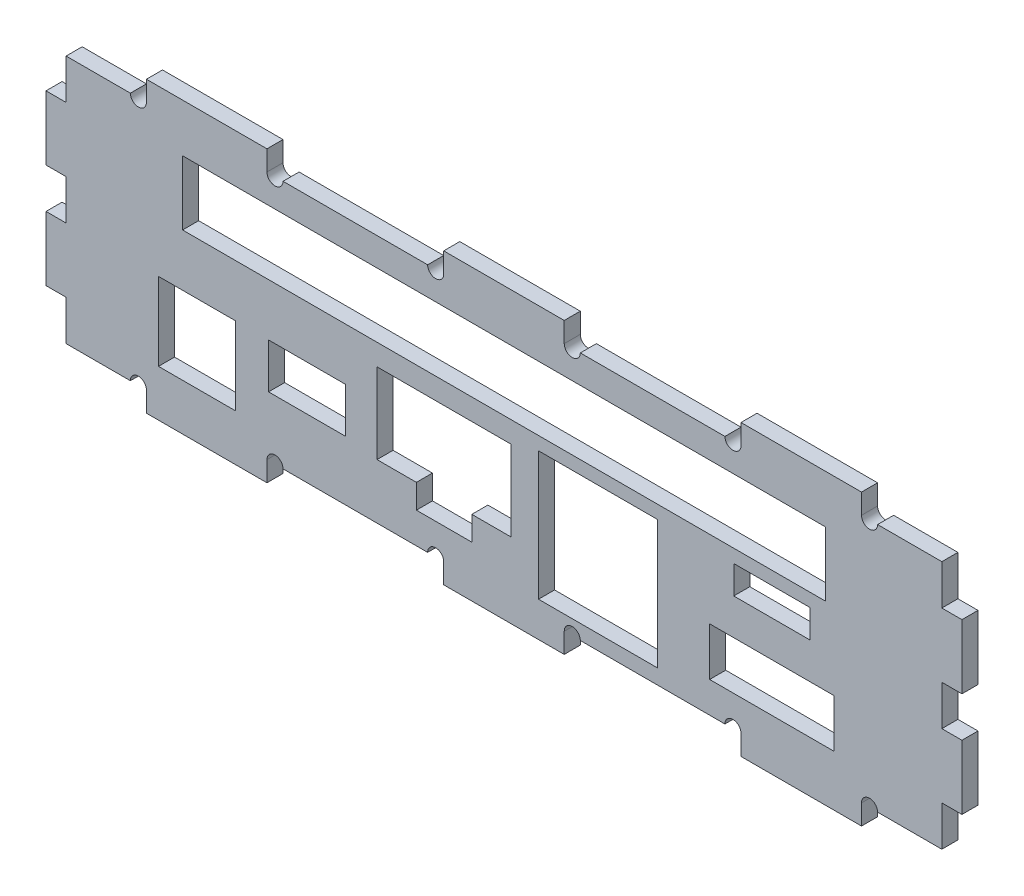
SolidWorks part; units mm, degrees
ref_plane "前视基准面" through (0, 0, 0) normal (0, 0, 1) x (1, 0, 0)
ref_plane "上视基准面" through (0, 0, 0) normal (0, 1, 0) x (1, 0, 0)
ref_plane "右视基准面" through (0, 0, 0) normal (1, 0, 0) x (0, 0, -1)
sketch "草图1" plane through (0, 0, 0) normal (0, 0, 1) x (1, 0, 0)
  line L0 (27.2, 3.55) -> (32.1, 3.55)
  line L1 (0, 0) -> (9.6, 0)
  line L2 (0, 0) -> (0, 9.7)
  line L3 (0, 9.7) -> (9.6, 9.7)
  line L4 (9.6, 0) -> (9.6, 9.7)
  line L5 (13.7, 9.7) -> (23.3, 9.7)
  line L6 (13.7, 9.7) -> (13.7, 4.1)
  line L7 (13.7, 4.1) -> (23.3, 4.1)
  line L8 (23.3, 9.7) -> (23.3, 4.1)
  line L10 (27.2, 3.55) -> (27.2, 13.55)
  line L11 (27.2, 13.55) -> (43.9, 13.55)
  line L12 (43.9, 3.55) -> (43.9, 13.55)
  line L13 (32.1, 3.55) -> (32.1, 0.55)
  line L14 (32.1, 0.55) -> (39, 0.55)
  line L15 (39, 0.55) -> (39, 3.55)
  line L16 (39, 3.55) -> (43.9, 3.55)
  line L18 (47.3, 14.55) -> (62.1, 14.55)
  line L19 (47.3, 14.55) -> (47.3, -1.45)
  line L20 (47.3, -1.45) -> (62.1, -1.45)
  line L21 (62.1, 14.55) -> (62.1, -1.45)
  line L22 (71.6, 14.55) -> (81.1, 14.55)
  line L23 (71.6, 14.55) -> (71.6, 11.05)
  line L24 (71.6, 11.05) -> (81.1, 11.05)
  line L25 (81.1, 14.55) -> (81.1, 11.05)
  line L26 (68.6, 6.55) -> (84.1, 6.55)
  line L27 (68.6, 6.55) -> (68.6, 0.55)
  line L28 (68.6, 0.55) -> (84.1, 0.55)
  line L29 (84.1, 6.55) -> (84.1, 0.55)
  line L30 (3, 16.2) -> (83, 16.2)
  line L31 (3, 16.2) -> (3, 24.2)
  line L32 (3, 24.2) -> (83, 24.2)
  line L33 (83, 16.2) -> (83, 24.2)
  line L34 (-11.5, -3.3) -> (97.5, -3.3)
  line L35 (-11.5, -3.3) -> (-11.5, 27.7)
  line L36 (-11.5, 27.7) -> (97.5, 27.7)
  line L37 (97.5, -3.3) -> (97.5, 27.7)
  dimension "D1" = 9.6
  dimension "D2" = 9.7
  dimension "D3" = 9.6
  dimension "D4" = 4.1
  dimension "D5" = 5.6
  dimension "D6" = 3.9
  dimension "D7" = 10
  dimension "D8" = 6.15
  dimension "D9" = 16.7
  dimension "D10" = 4.9
  dimension "D11" = 3
  dimension "D12" = 3.4
  dimension "D13" = 14.8
  dimension "D14" = 11
  dimension "D15" = 16
  dimension "D16" = 6.5
  dimension "D17" = 6
  dimension "D18" = 2
  dimension "D19" = 15.5
  dimension "D20" = 9.5
  dimension "D21" = 3
  dimension "D22" = 3.5
  dimension "D23" = 14.5
  dimension "D24" = 8
  dimension "D25" = 3
  dimension "D26" = 80
  dimension "D27" = 109
  dimension "D28" = 3.5
  dimension "D29" = 31
  dimension "D30" = 14.5
extrude "凸台-拉伸1" add sketch "草图1" along normal blind 2
sketch "草图2" plane through (0, 0, 2) normal (0, 0, 1) x (1, 0, 0)
  line L0 (-11.5, 27.7) -> (-11.5, -3.3) construction
  line L1 (-11.5, 22.7) -> (-14, 22.7)
  line L2 (-11.5, 22.7) -> (-11.5, 14.7)
  line L3 (-11.5, 14.7) -> (-14, 14.7)
  line L4 (-14, 22.7) -> (-14, 14.7)
  line L5 (97.5, 27.7) -> (-11.5, 27.7) construction
  line L6 (-11.5, 9.7) -> (-14, 9.7)
  line L7 (-11.5, 9.7) -> (-11.5, 1.7)
  line L8 (-11.5, 1.7) -> (-14, 1.7)
  line L9 (-14, 9.7) -> (-14, 1.7)
  line L10 (-11.5, -3.3) -> (97.5, -3.3) construction
  line L11 (43, 27.7) -> (43, -3.3) construction
  line L12 (100, 9.7) -> (100, 1.7)
  line L13 (97.5, 1.7) -> (100, 1.7)
  line L14 (97.5, 9.7) -> (97.5, 1.7)
  line L15 (97.5, 9.7) -> (100, 9.7)
  line L16 (100, 22.7) -> (100, 14.7)
  line L17 (97.5, 14.7) -> (100, 14.7)
  line L18 (97.5, 22.7) -> (97.5, 14.7)
  line L19 (97.5, 22.7) -> (100, 22.7)
  dimension "D1" = 8
  dimension "D2" = 5
  dimension "D3" = 5
  dimension "D4" = 8
  dimension "D5" = 2.5
  dimension "D6" = 2.5
extrude "凸台-拉伸2" add sketch "草图2" against normal up to surface (2 mm away) up to face at (43, 12.2, 0)
sketch "草图3" plane through (0, 0, 0) normal (0, 0, 1) x (1, 0, 0)
  line L2 (-1.5, 27.7) -> (13.5, 27.7)
  line L3 (-1.5, 27.7) -> (-1.5, 30.2)
  line L4 (-1.5, 30.2) -> (13.5, 30.2)
  line L5 (13.5, 27.7) -> (13.5, 30.2)
  line L6 (35.5, 27.7) -> (50.5, 27.7)
  line L7 (35.5, 27.7) -> (35.5, 30.2)
  line L8 (35.5, 30.2) -> (50.5, 30.2)
  line L9 (50.5, 27.7) -> (50.5, 30.2)
  line L10 (87.5, 27.7) -> (72.5, 27.7)
  line L11 (87.5, 27.7) -> (87.5, 30.2)
  line L12 (87.5, 30.2) -> (72.5, 30.2)
  line L13 (72.5, 27.7) -> (72.5, 30.2)
  line L15 (-11.5, 12.2) -> (97.5, 12.2) construction
  line L18 (72.5, -3.3) -> (72.5, -5.8)
  line L19 (87.5, -5.8) -> (72.5, -5.8)
  line L20 (87.5, -3.3) -> (87.5, -5.8)
  line L21 (87.5, -3.3) -> (72.5, -3.3)
  line L22 (50.5, -3.3) -> (50.5, -5.8)
  line L23 (35.5, -5.8) -> (50.5, -5.8)
  line L24 (35.5, -3.3) -> (35.5, -5.8)
  line L25 (35.5, -3.3) -> (50.5, -3.3)
  line L26 (13.5, -3.3) -> (13.5, -5.8)
  line L27 (-1.5, -5.8) -> (13.5, -5.8)
  line L28 (-1.5, -3.3) -> (-1.5, -5.8)
  line L29 (-1.5, -3.3) -> (13.5, -3.3)
  line L30 (-11.5, 14.7) -> (-11.5, 9.7) construction
  line L31 (97.5, 9.7) -> (97.5, 14.7) construction
  line L32 (-11.5, 27.7) -> (-11.5, 22.7) construction
  line L33 (97.5, 27.7) -> (-11.5, 27.7) construction
  line L34 (97.5, 22.7) -> (97.5, 27.7) construction
  point P18 (43, 30.2)
  dimension "D1" = 10
  dimension "D2" = 54.5
  dimension "D3" = 15
  dimension "D4" = 15
  dimension "D5" = 2.5
  dimension "D6" = 10
  dimension "D7" = 15
extrude "凸台-拉伸4" add sketch "草图3" along normal up to surface (2 mm away) up to face at (76.35, 3.55, 2)
sketch "草图4" plane through (0, 0, 0) normal (0, 0, 1) x (1, 0, 0)
  line L0 (-3.5, 27.7) -> (-1.5, 27.7)
  line L2 (6, 30.2) -> (6, -5.8) construction
  line L5 (15.5, 27.7) -> (13.5, 27.7)
  line L6 (24.5, 27.7) -> (24.5, -3.3) construction
  line L9 (33.5, 27.7) -> (35.5, 27.7)
  line L10 (43, 30.2) -> (43, -5.8) construction
  line L13 (52.5, 27.7) -> (50.5, 27.7)
  line L14 (70.5, 27.7) -> (72.5, 27.7)
  line L15 (89.5, 27.7) -> (87.5, 27.7)
  line L16 (-11.5, 12.2) -> (97.5, 12.2) construction
  line L19 (89.5, -3.3) -> (87.5, -3.3)
  line L20 (70.5, -3.3) -> (72.5, -3.3)
  line L21 (52.5, -3.3) -> (50.5, -3.3)
  line L22 (33.5, -3.3) -> (35.5, -3.3)
  line L23 (15.5, -3.3) -> (13.5, -3.3)
  line L24 (-3.5, -3.3) -> (-1.5, -3.3)
  line L25 (-11.5, 14.7) -> (-11.5, 9.7) construction
  line L26 (97.5, 9.7) -> (97.5, 14.7) construction
  line L27 (35.5, 27.7) -> (13.5, 27.7) construction
  line L28 (-1.5, 30.2) -> (13.5, 30.2) construction
  line L29 (35.5, 30.2) -> (50.5, 30.2) construction
  line L30 (50.5, -5.8) -> (35.5, -5.8) construction
  line L31 (13.5, -3.3) -> (35.5, -3.3) construction
  line L32 (13.5, -5.8) -> (-1.5, -5.8) construction
  arc A0 (-1.5, 27.7) -> (-3.5, 27.7) centre (-2.5, 27.7) cw
  arc A1 (13.5, 27.7) -> (15.5, 27.7) centre (14.5, 27.7) ccw
  arc A2 (35.5, 27.7) -> (33.5, 27.7) centre (34.5, 27.7) cw
  arc A3 (50.5, 27.7) -> (52.5, 27.7) centre (51.5, 27.7) ccw
  arc A4 (72.5, 27.7) -> (70.5, 27.7) centre (71.5, 27.7) cw
  arc A5 (87.5, 27.7) -> (89.5, 27.7) centre (88.5, 27.7) ccw
  arc A6 (87.5, -3.3) -> (89.5, -3.3) centre (88.5, -3.3) cw
  arc A7 (72.5, -3.3) -> (70.5, -3.3) centre (71.5, -3.3) ccw
  arc A8 (50.5, -3.3) -> (52.5, -3.3) centre (51.5, -3.3) cw
  arc A9 (35.5, -3.3) -> (33.5, -3.3) centre (34.5, -3.3) ccw
  arc A10 (13.5, -3.3) -> (15.5, -3.3) centre (14.5, -3.3) cw
  arc A11 (-1.5, -3.3) -> (-3.5, -3.3) centre (-2.5, -3.3) ccw
  dimension "D1" = 1
extrude "切除-拉伸2" cut sketch "草图4" along normal up to surface (2 mm away) up to face at (76.35, 3.55, 2)
